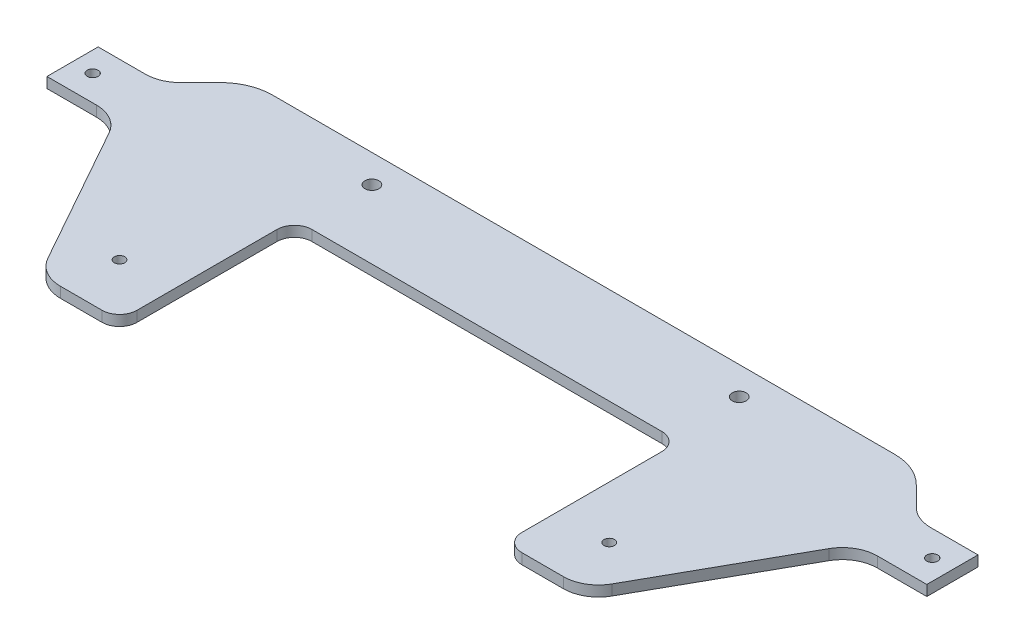
SolidWorks part; units mm, degrees
ref_plane "Alzado" through (0, 0, 0) normal (0, 0, 1) x (1, 0, 0)
ref_plane "Planta" through (0, 0, 0) normal (0, 1, 0) x (1, 0, 0)
ref_plane "Vista lateral" through (0, 0, 0) normal (1, 0, 0) x (0, 0, -1)
sketch "Croquis1" plane through (0, 0, 0) normal (0, 1, 0) x (1, 0, 0)
  line L0 (-27.8825, 0) -> (38.5584, 0) construction
  line L1 (-88.1, 42.3182) -> (88.1, 42.3182)
  line L2 (-77.75, -42.3182) -> (77.75, -42.3182)
  line L3 (-88.1, 42.3182) -> (-108.1, 22.3182)
  line L4 (-108.1, 22.3182) -> (-127.75, 22.3182)
  line L5 (0, 0) -> (0, 27.7067) construction
  line L6 (-127.75, 22.3182) -> (-127.75, 7.6818)
  line L7 (-127.75, 7.6818) -> (-105.75, 7.6818)
  line L8 (-105.75, 7.6818) -> (-77.75, -42.3182)
  line L9 (88.1, 42.3182) -> (108.1, 22.3182)
  line L10 (108.1, 22.3182) -> (127.75, 22.3182)
  line L11 (127.75, 22.3182) -> (127.75, 7.6818)
  line L12 (127.75, 7.6818) -> (105.75, 7.6818)
  line L13 (105.75, 7.6818) -> (77.75, -42.3182)
  dimension "D1" = 255.5
  dimension "D2" = 84.6363
  dimension "D3" = 19.65
  dimension "D4" = 22
  dimension "D5" = 22
  dimension "D6" = 50
  dimension "D7" = 50
  dimension "D8" = 50
  dimension "D9" = 20
  dimension "D10" = 20
extrude "Saliente-Extruir1" add sketch "Croquis1" along normal blind 3
fillet "Redondeo1" radius 10 8 edges at (88.1, 1.5, -42.3182) (-88.1, 1.5, -42.3182) (-77.75, 1.5, 42.3182) (77.75, 1.5, 42.3182) (108.1, 1.5, -22.3182) (105.75, 1.5, -7.6818) (-105.75, 1.5, -7.6818) (-108.1, 1.5, -22.3182)
sketch "Croquis2" plane through (0, 3, 0) normal (0, 1, 0) x (1, 0, 0)
  line L0 (0, 0) -> (0, -87.7887) construction
  line L1 (-119.9961, 22.3182) -> (-119.9961, 40.4374) construction
  line L2 (-112.2421, 22.3182) -> (-127.75, 22.3182) construction
  line L3 (-127.75, 15) -> (-123.2915, 15) construction
  line L4 (-127.75, 22.3182) -> (-127.75, 7.6818) construction
  line L5 (119.9961, 22.3182) -> (119.9961, 29.1715) construction
  line L6 (127.75, 22.3182) -> (112.2421, 22.3182) construction
  line L7 (115.6048, 15) -> (126.3231, 15) construction
  line L10 (-71.8888, -42.3182) -> (71.8888, -42.3182) construction
  circle A0 centre (70, -27.3182) radius 1.5
  circle A1 centre (-70, -27.3182) radius 1.5
  circle A2 centre (-119.9961, 15) radius 1.55
  circle A3 centre (119.9961, 15) radius 1.55
  circle A6 centre (-17.5, -17.3182) radius 1.5
  circle A7 centre (17.5, -17.3182) radius 1.5
  circle A8 centre (-17.5, -37.3182) radius 1.5
  circle A9 centre (17.5, -37.3182) radius 1.5
  dimension "D1" = 3.1
  dimension "D2" = 3.1
  dimension "D10" = 3
  dimension "D11" = 3
  dimension "D17" = 3
  dimension "D18" = 3
  dimension "D19" = 3
  dimension "D20" = 3
  dimension "D9" = 140
  dimension "D12" = 15
  dimension "D13" = 35
  dimension "D14" = 35
  dimension "D15" = 5
  dimension "D16" = 20
extrude "Cortar-Extruir1" cut sketch "Croquis2" against normal through all
sketch "Croquis4" plane through (0, 3, 0) normal (0, 1, 0) x (1, 0, 0)
  line L0 (-55, -42.3182) -> (-55, 7.6818)
  line L1 (-55, 7.6818) -> (55, 7.6818)
  line L2 (55, 7.6818) -> (55, -42.3182)
  line L3 (55, -42.3182) -> (-55, -42.3182)
  line L4 (0, 0) -> (0, 21.6247) construction
  line L5 (-71.8888, -42.3182) -> (71.8888, -42.3182) construction
  dimension "D1" = 110
  dimension "D2" = 50
extrude "Cortar-Extruir2" cut sketch "Croquis4" against normal through all
fillet "Redondeo2" radius 5 4 edges at (-55, 1.5, 42.3182) (55, 1.5, 42.3182) (55, 1.5, -7.6818) (-55, 1.5, -7.6818)
sketch "Croquis5" plane through (0, 3, 0) normal (0, 1, 0) x (1, 0, 0)
  line L0 (-127.75, 22.3182) -> (-127.75, 7.6818)
  line L1 (-127.75, 7.6818) -> (-123.75, 7.6818)
  line L2 (-127.75, 7.6818) -> (-111.6112, 7.6818) construction
  line L3 (-123.75, 7.6818) -> (-123.75, 22.3182)
  line L4 (-112.2421, 22.3182) -> (-127.75, 22.3182) construction
  line L5 (-123.75, 22.3182) -> (-127.75, 22.3182)
  line L6 (127.75, 22.3182) -> (127.75, 7.6818)
  line L7 (127.75, 7.6818) -> (123.75, 7.6818)
  line L8 (111.6112, 7.6818) -> (127.75, 7.6818) construction
  line L9 (123.75, 7.6818) -> (123.75, 22.3182)
  line L10 (127.75, 22.3182) -> (112.2421, 22.3182) construction
  line L11 (123.75, 22.3182) -> (127.75, 22.3182)
  dimension "D1" = 4
  dimension "D2" = 4
extrude "Cortar-Extruir3" cut sketch "Croquis5" against normal through all
sketch "Croquis6" plane through (123.75, 0, 0) normal (1, 0, 0) x (0, 0, -1)
  line L0 (7.6818, 3) -> (22.3182, 3)
  line L1 (22.3182, 3) -> (22.3182, 0)
  line L2 (22.3182, 0) -> (7.6818, 0)
  line L3 (22.3182, 0) -> (7.6818, 0) construction
  line L4 (7.6818, 0) -> (7.6818, 3) construction
  line L5 (7.6818, 3) -> (7.6818, 0)
extrude "Saliente-Extruir2" add sketch "Croquis6" along normal blind 2
sketch "Croquis8" plane through (-123.75, 0, 0) normal (-1, 0, 0) x (0, 0, 1)
  line L4 (-7.6818, 3) -> (-22.3182, 3)
  line L5 (-22.3182, 3) -> (-22.3182, 0)
  line L6 (-22.3182, 0) -> (-7.6818, 0)
  line L7 (-7.6818, 0) -> (-7.6818, 3)
  line L8 (-7.6818, 3) -> (-22.3182, 3)
  line L9 (-22.3182, 3) -> (-22.3182, 0)
  line L10 (-22.3182, 0) -> (-7.6818, 0)
  line L11 (-7.6818, 0) -> (-7.6818, 3)
  dimension "D1" = 0
extrude "Saliente-Extruir3" add sketch "Croquis8" along normal blind 2
sketch "Croquis9" plane through (0, 3, 0) normal (0, 1, 0) x (1, 0, 0)
  line L7 (-98.1, 66.4057) -> (98.1, 66.4057)
  line L8 (98.1, 66.4057) -> (98.1, 35.3182)
  line L9 (0, 0) -> (0, 90.0009) construction
  line L15 (-98.1, 66.4057) -> (-98.1, 35.3182)
  line L16 (-98.1, 35.3182) -> (98.1, 35.3182)
  line L17 (83.9579, 42.3182) -> (-83.9579, 42.3182) construction
  dimension "D1" = 7
extrude "Cortar-Extruir4" cut sketch "Croquis9" against normal through all
fillet "Redondeo3" [suppressed] radius 50
sketch "Croquis10" plane through (0, 3, 0) normal (0, 1, 0) x (1, 0, 0)
  line L0 (0, 0) -> (0, 30.8751) construction
  line L2 (-95.1, 35.3182) -> (95.1, 35.3182) construction
  circle A0 centre (-52.5, 27.3182) radius 2
  circle A1 centre (52.5, 27.3182) radius 2
  dimension "D1" = 4
  dimension "D2" = 4
  dimension "D3" = 105
  dimension "D4" = 8
  dimension "D5" = 8
extrude "Cortar-Extruir5" cut sketch "Croquis10" against normal through all
fillet "Redondeo6" radius 15 2 edges at (95.1, 1.5, -35.3182) (-95.1, 1.5, -35.3182)
